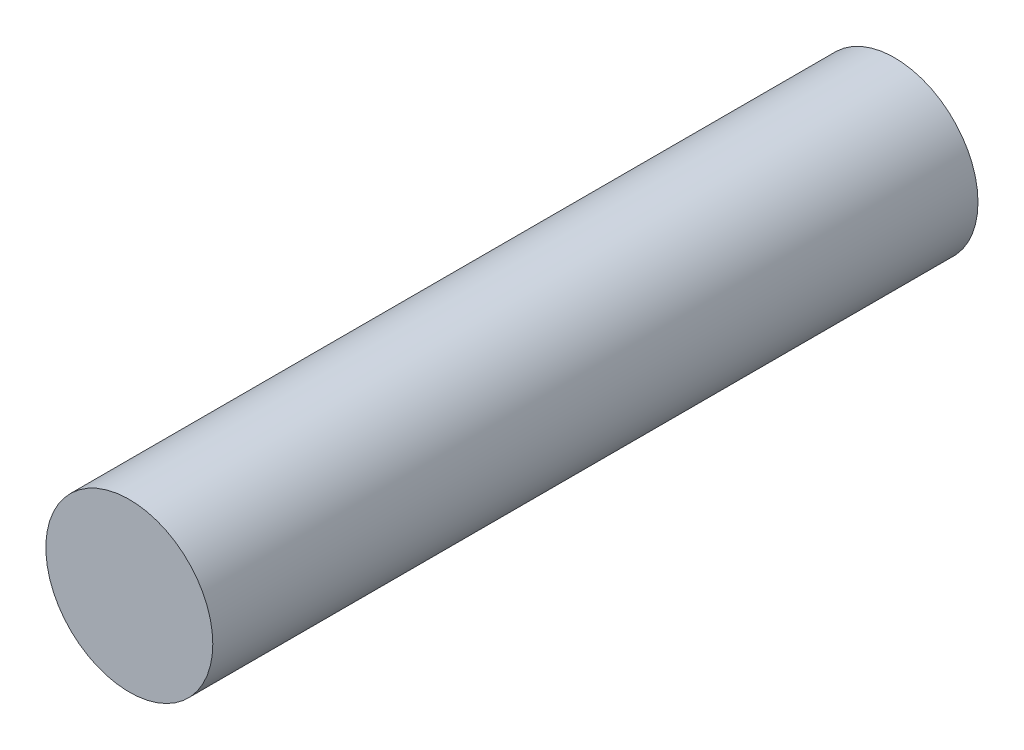
SolidWorks part; units mm, degrees
material "1060 Alloy"
ref_plane "Front Plane" through (0, 0, 0) normal (0, 0, 1) x (1, 0, 0)
ref_plane "Top Plane" through (0, 0, 0) normal (0, 1, 0) x (1, 0, 0)
ref_plane "Right Plane" through (0, 0, 0) normal (1, 0, 0) x (0, 0, -1)
sketch "Sketch1" plane through (0, 0, 0) normal (0, 0, 1) x (1, 0, 0)
  circle A0 centre (0, 0) radius 6
  dimension "D1" = 12
extrude "Boss-Extrude1" add sketch "Sketch1" along normal blind 55
